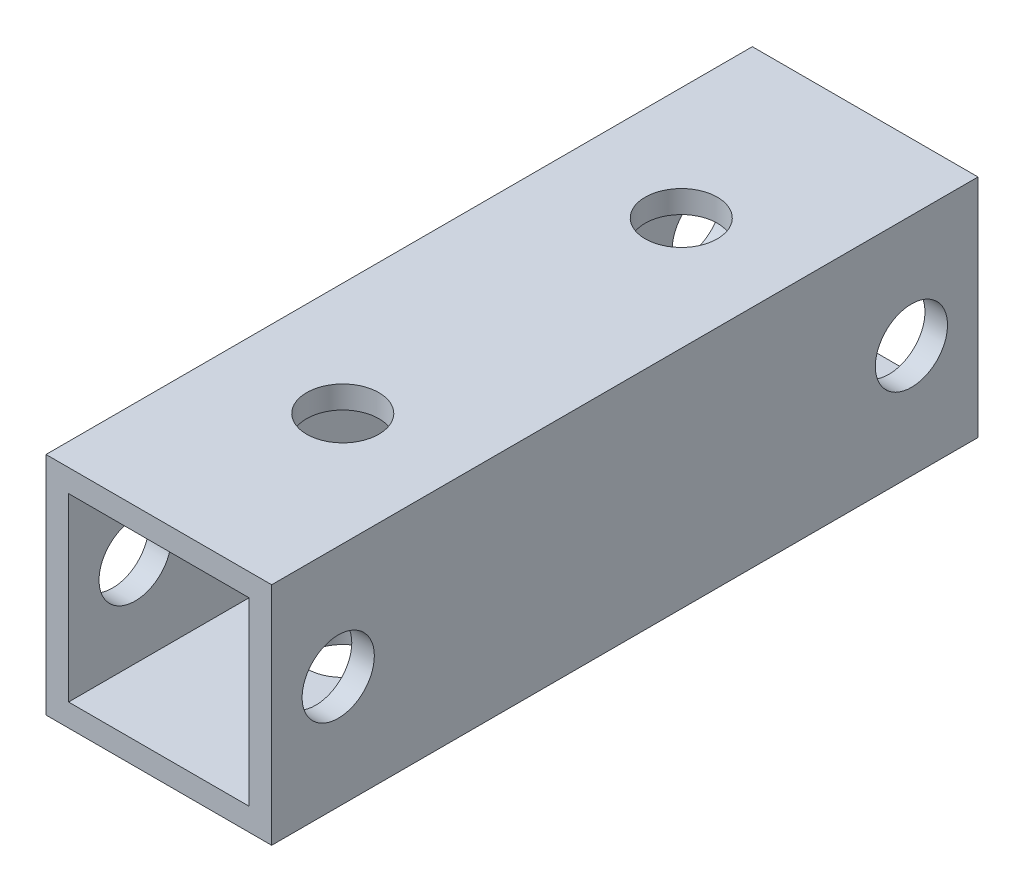
SolidWorks part; units mm, degrees
material "5052-H34"
ref_plane "正面" through (0, 0, 0) normal (0, 0, 1) x (1, 0, 0)
ref_plane "平面" through (0, 0, 0) normal (0, 1, 0) x (1, 0, 0)
ref_plane "右側面" through (0, 0, 0) normal (1, 0, 0) x (0, 0, -1)
sketch "ｽｹｯﾁ2" plane through (0, 0, 0) normal (0, 0, 1) x (1, 0, 0)
  line L1 (0, 0) -> (10, 0)
  line L2 (0, 0) -> (0, 10)
  line L3 (0, 10) -> (10, 10)
  line L4 (10, 0) -> (10, 10)
  dimension "D1" = 10
  dimension "D2" = 10
extrude "押し出し-薄板1" add sketch "ｽｹｯﾁ2" along normal blind 31.3 thin thin type one direction reverse wall 1
sketch "ｽｹｯﾁ3" plane through (0, 10, 0) normal (0, 1, 0) x (1, 0, 0)
  line L0 (5, 0) -> (5, -31.3) construction
  line L1 (10, 0) -> (0, 0) construction
  line L2 (10, -31.3) -> (0, -31.3) construction
  line L3 (10, -15.65) -> (0, -15.65) construction
  line L4 (10, -31.3) -> (10, 0) construction
  line L5 (0, -31.3) -> (0, 0) construction
  circle A0 centre (5, -23.15) radius 1.6
  circle A1 centre (5, -8.15) radius 1.6
  point P10 (0, -15.65)
  dimension "D1" = 3.2
  dimension "D2" = 15
extrude "ｶｯﾄ - 押し出し1" cut sketch "ｽｹｯﾁ3" against normal up to surface (10 mm away) up to face at (5, 0, 15.65)
sketch "ｽｹｯﾁ4" plane through (10, 0, 0) normal (1, 0, 0) x (0, 0, -1)
  line L0 (-31.3, 5) -> (0, 5) construction
  line L1 (-31.3, 0) -> (-31.3, 10) construction
  line L2 (0, 0) -> (0, 10) construction
  line L3 (-15.65, 0) -> (-15.65, 10) construction
  line L4 (-31.3, 0) -> (0, 0) construction
  line L5 (-31.3, 10) -> (0, 10) construction
  circle A0 centre (-28.35, 5) radius 1.6
  circle A1 centre (-2.95, 5) radius 1.6
  dimension "D1" = 3.2
  dimension "D2" = 25.4
extrude "ｶｯﾄ - 押し出し2" cut sketch "ｽｹｯﾁ4" against normal up to surface (10 mm away) up to face at (0, 5, 15.65)
